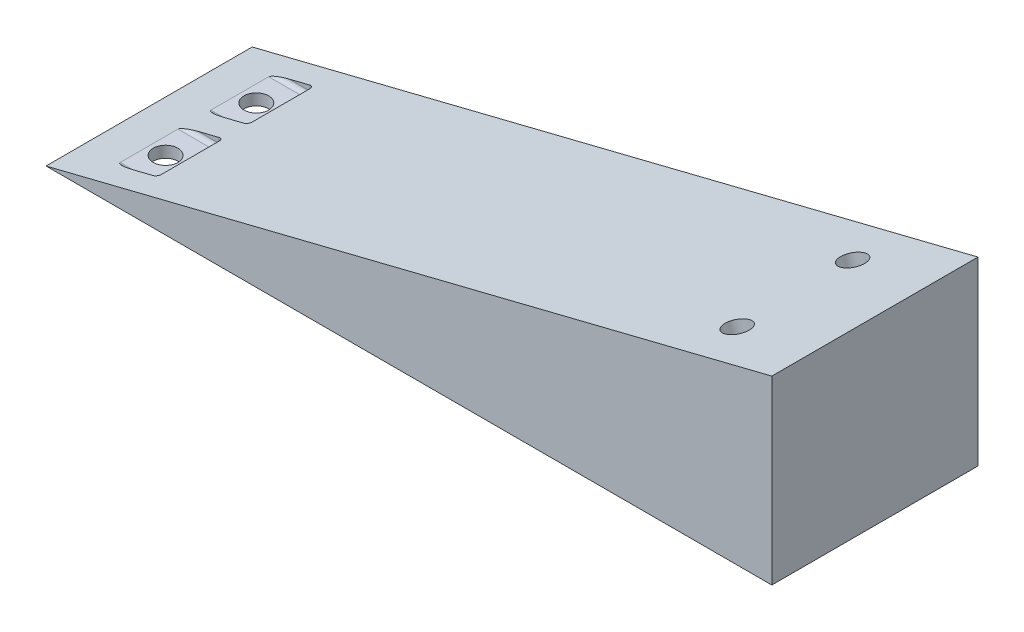
SolidWorks part; units mm, degrees
material "ABS"
ref_plane "前视基准面" through (0, 0, 0) normal (0, 0, 1) x (1, 0, 0)
ref_plane "上视基准面" through (0, 0, 0) normal (0, 1, 0) x (1, 0, 0)
ref_plane "右视基准面" through (0, 0, 0) normal (1, 0, 0) x (0, 0, -1)
sketch "草图1" plane through (0, 0, 0) normal (0, 0, 1) x (1, 0, 0)
  line L0 (0, 0) -> (-88, 0)
  line L1 (-88, 0) -> (0, 21.9409)
  line L2 (0, 21.9409) -> (0, 0)
  dimension "D1" = 88
  dimension "D2" = 14
extrude "凸台-拉伸1" add sketch "草图1" along normal blind 25
ref_plane "基准面1" through (0, 0, 22) normal (0, 0, 1) x (1, 0, 0)
sketch "草图2" plane through (0, 0, 0) normal (0, -1, 0) x (1, 0, 0)
  line L0 (0, 19.5) -> (-88, 19.5) construction
  line L1 (0, 25) -> (0, 0) construction
  line L3 (-88, 12.5) -> (0, 12.5) construction
  line L4 (-88, 25) -> (-88, 0) construction
  circle A0 centre (-7.5, 19.5) radius 1.5
  circle A1 centre (-7.5, 5.5) radius 1.5
  dimension "D1" = 3
  dimension "D2" = 7.5
  dimension "D3" = 7
extrude "切除-拉伸1" cut sketch "草图2" against normal blind 8
sketch "草图3" plane through (-5.1503, 20.6567, 0) normal (-0.2419, 0.9703, 0) x (0.9703, 0.2419, 0)
  line L0 (6.1028, -5.5) -> (-85.0015, -5.5) construction
  line L1 (5.308, -25) -> (5.308, 0) construction
  line L3 (5.308, -12.5) -> (-85.386, -12.5) construction
  line L4 (-85.386, -25) -> (-85.386, 0) construction
  circle A0 centre (-4.692, -5.5) radius 1.5
  circle A1 centre (-4.692, -19.5) radius 1.5
  dimension "D1" = 3
  dimension "D2" = 10
  dimension "D3" = 7
extrude "切除-拉伸2" cut sketch "草图3" against normal blind 8
sketch "草图5" plane through (0, 0, 22) normal (0, 0, 1) x (1, 0, 0)
  line L0 (0, 21.9409) -> (-88, 0) construction
  line L1 (0, 21.9409) -> (-88, 0)
  line L2 (-82.5, 1.3713) -> (-77.5, 1.3713)
  line L3 (-77.5, 1.3713) -> (-77.5, 2.6179)
  point P5 (-80, 1.3713)
  dimension "D1" = 8
  dimension "D2" = 5
extrude "切除-拉伸3" cut sketch "草图5" against normal blind 8 contours L2 L3 L1
sketch "草图6" plane through (0, 1.3713, 0) normal (0, 1, 0) x (1, 0, 0)
  line L0 (-80.5, -15) -> (-80.5, -21) construction
  line L1 (0, -25) -> (-88, -25) construction
  line L3 (-80, 0) -> (-80, -21) construction
  line L4 (-82.5, -14) -> (-82.5, -22) construction
  circle A0 centre (-80.5, -18) radius 1.5
  point P2 (0, 0)
  point P10 (0, 0)
  point P11 (0, 0)
  point P13 (0, 0)
  point P14 (-80, 0)
  point P15 (0, 0)
  point P16 (0, 0)
  dimension "D1" = 3
  dimension "D2" = 0.5
  dimension "D3" = 2.5
  dimension "D4" = 7
extrude "切除-拉伸4" cut sketch "草图6" against normal through all
ref_plane "基准面2" through (0, 0, 12.5) normal (0, 0, 1) x (1, 0, 0)
mirror "镜向1" about plane through (0, 0, 12.5) normal (0, 0, 1) of "切除-拉伸4", "切除-拉伸3"
fillet "圆角1" radius 0.5 10 edges at (-77.5, 1.9946, 14) (-80, 1.3713, 22) (-80, 1.3713, 14) (-77.5, 1.3713, 18) (-77.5, 1.9946, 22) (-80, 1.3713, 11) (-77.5, 1.9946, 11) (-80, 1.3713, 3) (-77.5, 1.9946, 3) (-77.5, 1.3713, 7)
